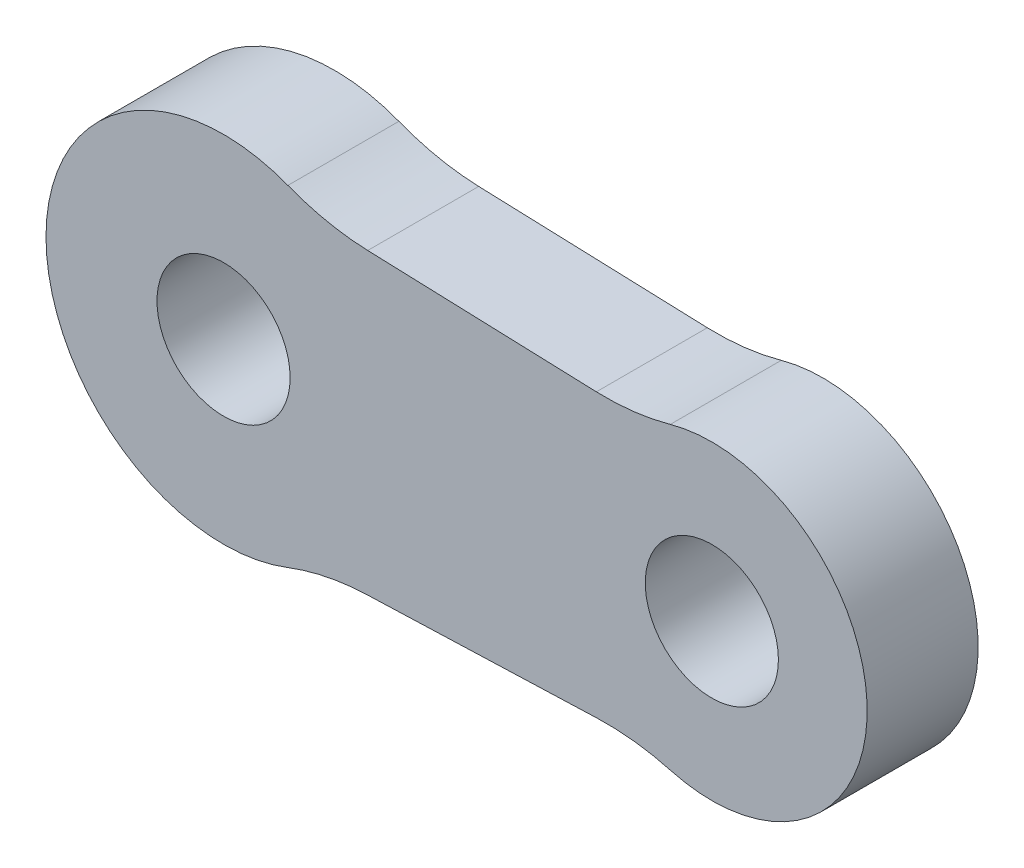
SolidWorks part; units mm, degrees
ref_plane "Front Plane" through (0, 0, 0) normal (0, 0, 1) x (1, 0, 0)
ref_plane "Top Plane" through (0, 0, 0) normal (0, 1, 0) x (1, 0, 0)
ref_plane "Right Plane" through (0, 0, 0) normal (1, 0, 0) x (0, 0, -1)
sketch "Sketch1" plane through (0, 0, 0) normal (0, 0, 1) x (1, 0, 0)
  line L0 (32.4799, 33.5781) -> (83.9871, 31.7563)
  line L1 (32.2284, -33.673) -> (84.235, -31.8269)
  circle A0 centre (0, 0) radius 15
  arc A1 (14.4943, 37.2816) -> (14.3914, -37.3214) centre (0, 0) ccw
  circle A2 centre (110, 0) radius 15
  arc A3 (100.7391, -33.7526) -> (100.6399, 33.7252) centre (110, 0) ccw
  arc A4 (83.9871, 31.7563) -> (100.6399, 33.7252) centre (85.9312, 86.7219) ccw
  arc A5 (84.235, -31.8269) -> (100.7391, -33.7526) centre (86.1861, -86.7923) cw
  arc A6 (32.2284, -33.673) -> (14.3914, -37.3214) centre (34.1795, -88.6384) ccw
  arc A7 (32.4799, 33.5781) -> (14.4943, 37.2816) centre (34.424, 88.5437) cw
  dimension "D1" = 110
  dimension "D2" = 30
  dimension "D3" = 30
  dimension "D4" = 80
  dimension "D5" = 70
  dimension "D6" = 35
  dimension "D7" = 55
extrude "Boss-Extrude1" add sketch "Sketch1" along normal blind 25 contours A0 | A1 A6 L1 A5 A3 A4 L0 A7 | A2
